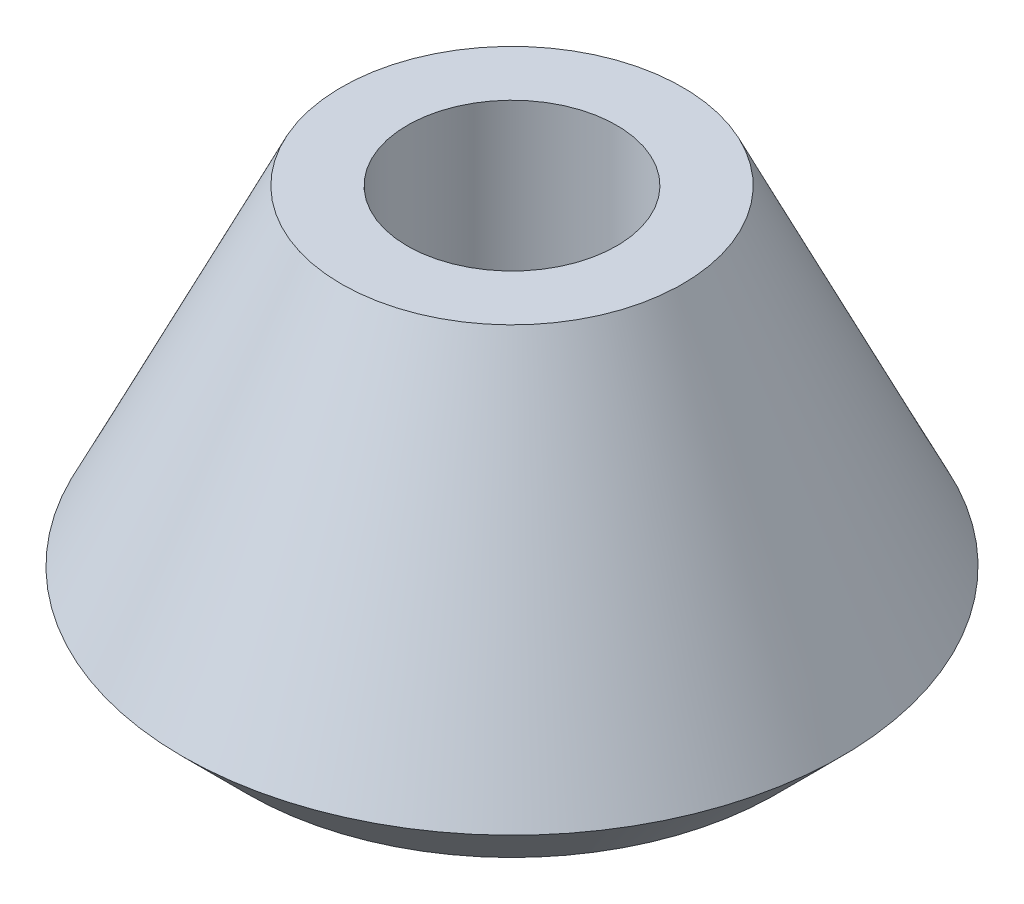
SolidWorks part; units mm, degrees
material "Rubber"
ref_plane "Front Plane" through (0, 0, 0) normal (0, 0, 1) x (1, 0, 0)
ref_plane "Top Plane" through (0, 0, 0) normal (0, 1, 0) x (1, 0, 0)
ref_plane "Right Plane" through (0, 0, 0) normal (1, 0, 0) x (0, 0, -1)
sketch "Sketch1" plane through (0, 0, 0) normal (0, 0, 1) x (1, 0, 0)
  line L0 (0, 4.0481) -> (0, -19.1294) construction
  line L1 (7.9375, 0) -> (7.9375, 30)
  line L2 (7.9375, 30) -> (12.9375, 30)
  line L3 (12.9375, 30) -> (25, 5)
  line L4 (25, 5) -> (20, 0)
  line L5 (20, 0) -> (7.9375, 0)
  dimension "D1" = 15.875
  dimension "D2" = 30
  dimension "D3" = 40
  dimension "D4" = 50
  dimension "D5" = 45
  dimension "D6" = 5
revolve "Revolve1" add sketch "Sketch1" angle 360 about L0
